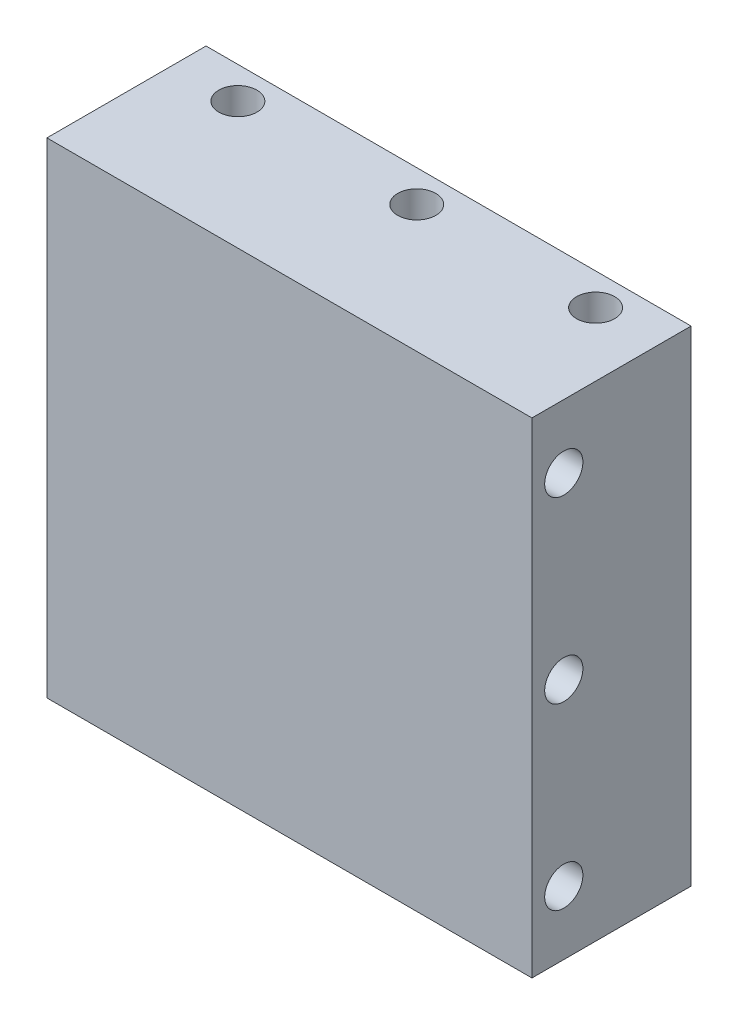
SolidWorks part; units mm, degrees
ref_plane "Front Plane" through (0, 0, 0) normal (0, 0, 1) x (1, 0, 0)
ref_plane "Top Plane" through (0, 0, 0) normal (0, 1, 0) x (1, 0, 0)
ref_plane "Right Plane" through (0, 0, 0) normal (1, 0, 0) x (0, 0, -1)
sketch "Sketch1" plane through (0, 0, 0) normal (0, 0, 1) x (1, 0, 0)
  line L1 (-76.2, 76.2) -> (76.2, 76.2)
  line L2 (-76.2, 76.2) -> (-76.2, -76.2)
  line L3 (-76.2, -76.2) -> (76.2, -76.2)
  line L4 (76.2, 76.2) -> (76.2, -76.2)
  line L5 (-76.2, 76.2) -> (76.2, -76.2) construction
  line L6 (-76.2, -76.2) -> (76.2, 76.2) construction
  point P0 (0, 0)
  dimension "D1" = 152.4
extrude "Boss-Extrude1" add sketch "Sketch1" along normal blind 50
sketch "Sketch2" plane through (76.2, 0, 0) normal (1, 0, 0) x (0, 0, -1)
  line L0 (-50, -76.2) -> (-50, 76.2) construction
  line L1 (-50, 76.2) -> (0, 76.2) construction
  line L2 (-50, -76.2) -> (0, -76.2) construction
  circle A0 centre (-40, 56.2) radius 6
  circle A1 centre (-40, 0) radius 6
  circle A2 centre (-40, -56.2) radius 6
  point P6 (0, 0)
  point P7 (0, 0)
  point P8 (0, 0)
  dimension "D1" = 10
  dimension "D2" = 10
  dimension "D3" = 10
  dimension "D4" = 20
  dimension "D5" = 20
  dimension "D6" = 112.4
  dimension "D7" = 56.2
extrude "Cut-Extrude1" cut sketch "Sketch2" against normal through all
sketch "Sketch4" plane through (0, 76.2, 0) normal (0, 1, 0) x (1, 0, 0)
  line L0 (76.2, 0) -> (-76.2, 0) construction
  line L1 (-76.2, -50) -> (-76.2, 0) construction
  line L2 (76.2, -50) -> (76.2, 0) construction
  circle A0 centre (-56.2, -10) radius 6
  circle A1 centre (0, -10) radius 6
  circle A2 centre (56.2, -10) radius 6
  point P6 (0, 0)
  dimension "D1" = 12
  dimension "D2" = 10
  dimension "D3" = 20
  dimension "D4" = 20
  dimension "D5" = 10
  dimension "D6" = 10
  dimension "D7" = 112.4
  dimension "D8" = 56.2
extrude "Cut-Extrude2" cut sketch "Sketch4" against normal through all
